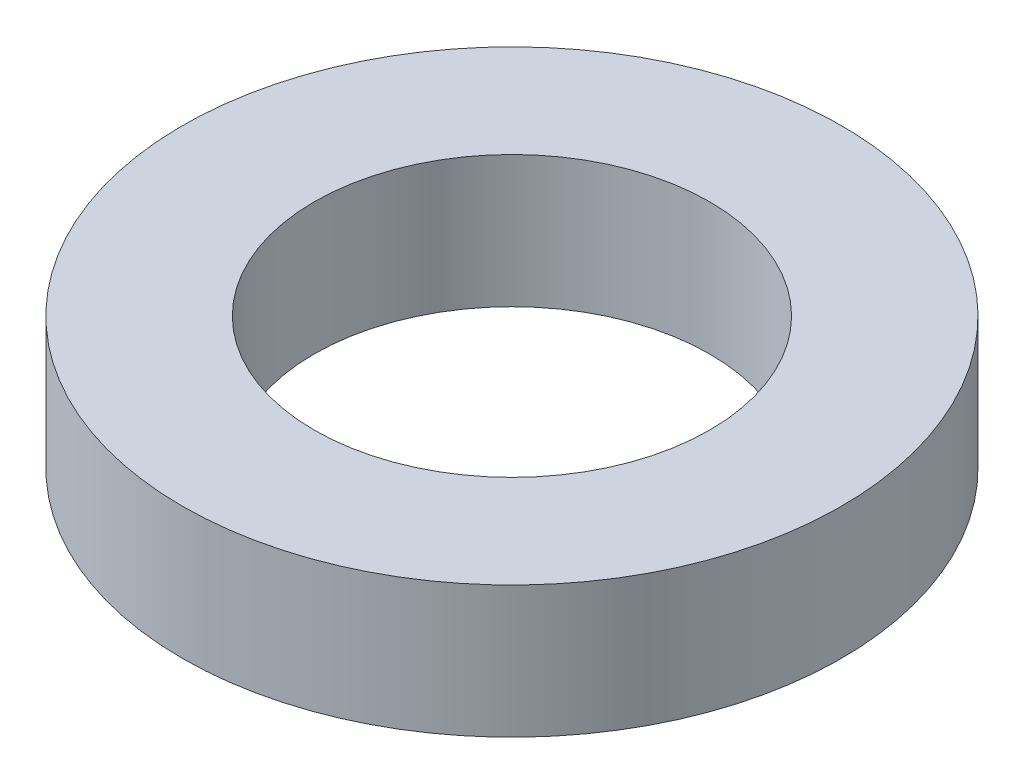
SolidWorks part; units mm, degrees
ref_plane "Alzado" through (0, 0, 0) normal (0, 0, 1) x (1, 0, 0)
ref_plane "Planta" through (0, 0, 0) normal (0, 1, 0) x (1, 0, 0)
ref_plane "Vista lateral" through (0, 0, 0) normal (1, 0, 0) x (0, 0, -1)
sketch "Croquis1" plane through (0, 0, 0) normal (0, 1, 0) x (1, 0, 0)
  circle A0 centre (0, 0) radius 1.5
  circle A1 centre (0, 0) radius 2.5
  dimension "D1" = 3
  dimension "D2" = 5
extrude "Saliente-Extruir1" add sketch "Croquis1" along normal blind 1
